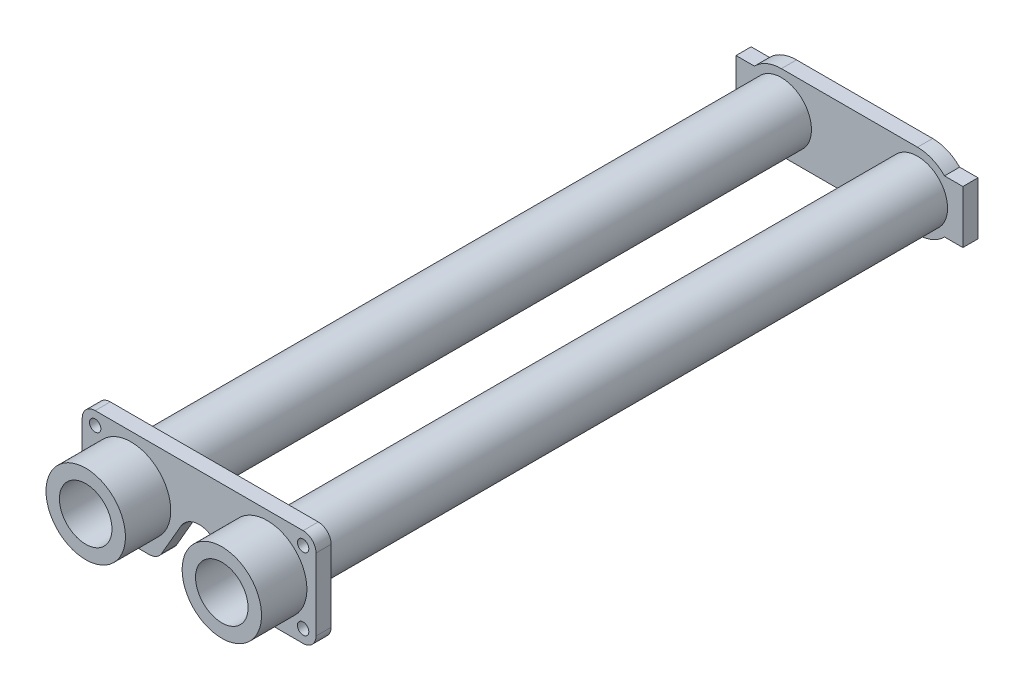
SolidWorks part; units mm, degrees
ref_plane "front" through (0, 0, 0) normal (0, 0, 1) x (1, 0, 0)
ref_plane "top" through (0, 0, 0) normal (0, 1, 0) x (1, 0, 0)
ref_plane "right" through (0, 0, 0) normal (1, 0, 0) x (0, 0, -1)
sketch "L2D Layout front." plane through (0, 0, 0) normal (0, 0, 1) x (1, 0, 0)
  line L0 (87.3125, 41.021) -> (-87.3125, 41.021)
  line L1 (-98.171, 30.1625) -> (-98.171, -30.1625)
  line L2 (-87.3125, -41.021) -> (-42.161, -41.021)
  line L3 (98.171, -30.1625) -> (98.171, 30.1625)
  line L5 (-87.3125, -38.4187) -> (-80.1624, -34.2906) construction
  line L6 (-80.1624, -34.2906) -> (-80.1624, -26.0344) construction
  line L7 (-80.1624, -26.0344) -> (-87.3125, -21.9063) construction
  line L8 (-87.3125, -21.9063) -> (-94.4626, -26.0344) construction
  line L9 (-94.4626, -26.0344) -> (-94.4626, -34.2906) construction
  line L10 (-94.4626, -34.2906) -> (-87.3125, -38.4187) construction
  line L11 (-15.3429, -7.0167) -> (-31.3825, -34.798)
  line L12 (31.3825, -34.798) -> (15.3429, -7.0168)
  line L13 (42.161, -41.021) -> (87.3125, -41.021)
  line L14 (0, -20.3188) -> (0, -32.9867) construction
  arc A0 (87.3125, 41.021) -> (98.171, 30.1625) centre (87.3125, 30.1625) cw
  circle A1 centre (-57.15, 0) radius 25.2349
  circle A2 centre (-87.3125, -30.1625) radius 7.9375 construction
  circle A3 centre (-87.3125, -30.1625) radius 7.1501 construction
  arc A4 (-87.3125, 41.021) -> (-98.171, 30.1625) centre (-87.3125, 30.1625) ccw
  arc A5 (-98.171, -30.1625) -> (-87.3125, -41.021) centre (-87.3125, -30.1625) ccw
  arc A6 (87.3125, -41.021) -> (98.171, -30.1625) centre (87.3125, -30.1625) ccw
  circle A7 centre (0, 15.875) radius 6.3627
  circle A8 centre (-87.3125, -30.1625) radius 4.7879
  circle A9 centre (-87.3125, 30.1625) radius 4.7879
  circle A10 centre (87.3125, -30.1625) radius 4.7879
  circle A11 centre (87.3125, 30.1625) radius 4.7879
  circle A13 centre (57.15, 0) radius 25.2349
  circle A14 centre (0, 15.875) radius 9.525
  circle A15 centre (57.15, 0) radius 33.3375
  circle A16 centre (-57.15, 0) radius 33.3375
  arc A17 (15.3429, -7.0168) -> (-15.3429, -7.0167) centre (0, -15.875) ccw
  arc A18 (-42.161, -41.021) -> (-31.3825, -34.798) centre (-42.161, -28.575) ccw
  arc A19 (31.3825, -34.798) -> (42.161, -41.021) centre (42.161, -28.575) ccw
  circle A21 centre (-17.4752, 3.175) radius 3.175
  dimension "D1" = 10.8585
  dimension "D6" = 50.4698
  dimension "D7" = 57.15
  dimension "D12" = 9.5758
  dimension "D13" = 15.875
  dimension "D14" = 14.3002
  dimension "D18" = 12.7254
  dimension "D19" = 19.05
  dimension "D17" = 66.675
  dimension "D21" = 17.7165
  dimension "D22" = 12.446
  dimension "D26" = 17.4752
  dimension "D16" = 6.35
  dimension "D2" = 196.342
  dimension "D3" = 87.3125
  dimension "D4" = 15.875
  dimension "D5" = 57.15
  dimension "D8" = 30.1625
  dimension "D9" = 174.625
  dimension "D10" = 87.3125
  dimension "D11" = 30.1625
  dimension "D15" = 82.042
  dimension "D20" = 15.875
  dimension "D23" = 30
  dimension "D24" = 30
  dimension "D25" = 3.175
sketch "Sketch1" plane through (0, 0, 0) normal (0, 0, 1) x (1, 0, 0)
  line L0 (-98.171, 30.1625) -> (-98.171, -30.1625) construction
  line L5 (-87.3125, -41.021) -> (-42.161, -41.021) construction
  line L6 (-15.3429, -7.0167) -> (-31.3825, -34.798) construction
  line L7 (31.3825, -34.798) -> (15.3429, -7.0168) construction
  line L8 (42.161, -41.021) -> (87.3125, -41.021) construction
  line L9 (98.171, -30.1625) -> (98.171, 30.1625) construction
  line L10 (87.3125, 41.021) -> (-87.3125, 41.021) construction
  line L11 (-98.171, 30.1625) -> (-98.171, -30.1625)
  line L12 (-87.3125, -41.021) -> (-42.161, -41.021)
  line L13 (-15.3429, -7.0167) -> (-31.3825, -34.798)
  line L14 (31.3825, -34.798) -> (15.3429, -7.0168)
  line L15 (42.161, -41.021) -> (87.3125, -41.021)
  line L16 (98.171, -30.1625) -> (98.171, 30.1625)
  line L17 (87.3125, 41.021) -> (-87.3125, 41.021)
  arc A4 (-87.3125, 41.021) -> (-98.171, 30.1625) centre (-87.3125, 30.1625) ccw construction
  arc A5 (-98.171, -30.1625) -> (-87.3125, -41.021) centre (-87.3125, -30.1625) ccw construction
  arc A6 (-42.161, -41.021) -> (-31.3825, -34.798) centre (-42.161, -28.575) ccw construction
  arc A7 (15.3429, -7.0168) -> (-15.3429, -7.0167) centre (0, -15.875) ccw construction
  arc A8 (31.3825, -34.798) -> (42.161, -41.021) centre (42.161, -28.575) ccw construction
  arc A9 (87.3125, -41.021) -> (98.171, -30.1625) centre (87.3125, -30.1625) ccw construction
  arc A10 (98.171, 30.1625) -> (87.3125, 41.021) centre (87.3125, 30.1625) ccw construction
  arc A11 (-87.3125, 41.021) -> (-98.171, 30.1625) centre (-87.3125, 30.1625) ccw
  arc A12 (-98.171, -30.1625) -> (-87.3125, -41.021) centre (-87.3125, -30.1625) ccw
  arc A13 (-42.161, -41.021) -> (-31.3825, -34.798) centre (-42.161, -28.575) ccw
  arc A14 (15.3429, -7.0168) -> (-15.3429, -7.0167) centre (0, -15.875) ccw
  arc A15 (31.3825, -34.798) -> (42.161, -41.021) centre (42.161, -28.575) ccw
  arc A16 (87.3125, -41.021) -> (98.171, -30.1625) centre (87.3125, -30.1625) ccw
  arc A17 (98.171, 30.1625) -> (87.3125, 41.021) centre (87.3125, 30.1625) ccw
extrude "Extrude1" add sketch "Sketch1" against normal blind 12.7
sketch "Sketch27" plane through (0, 0, 0) normal (0, 0, 1) x (1, 0, 0)
  circle A2 centre (57.15, 0) radius 33.3375 construction
  circle A3 centre (-57.15, 0) radius 33.3375 construction
  circle A4 centre (-57.15, 0) radius 33.3375
  circle A5 centre (57.15, 0) radius 33.3375
  point P6 (-57.15, 33.3375)
  point P7 (57.15, 33.3375)
extrude "Extrude3" add sketch "Sketch27" along normal blind 38.1
sketch "Sketch29" plane through (0, 0, 0) normal (0, 0, 1) x (1, 0, 0)
  circle A0 centre (-87.3125, -30.1625) radius 4.7879 construction
  circle A1 centre (87.3125, -30.1625) radius 4.7879 construction
  circle A2 centre (87.3125, 30.1625) radius 4.7879 construction
  circle A3 centre (-87.3125, 30.1625) radius 4.7879 construction
  circle A4 centre (57.15, 0) radius 25.2349 construction
  circle A6 centre (-57.15, 0) radius 25.2349 construction
  circle A7 centre (-87.3125, -30.1625) radius 4.7879
  circle A8 centre (87.3125, -30.1625) radius 4.7879
  circle A9 centre (87.3125, 30.1625) radius 4.7879
  circle A10 centre (-87.3125, 30.1625) radius 4.7879
  circle A11 centre (57.15, 0) radius 25.2349
  circle A13 centre (-57.15, 0) radius 25.2349
extrude "Cut-Extrude5" cut sketch "Sketch29" against normal mid plane 101.6
sketch "Sketch41" plane through (0, 0, 38.1) normal (0, 0, -1) x (-1, 0, 0)
  circle A0 centre (-57.15, 0) radius 25.2349 construction
  circle A1 centre (57.15, 0) radius 25.2349 construction
  circle A2 centre (-57.15, 0) radius 25.2349
  circle A3 centre (57.15, 0) radius 25.2349
  circle A6 centre (-57.15, 0) radius 22.0599
  circle A7 centre (-57.15, 0) radius 22.0599
  circle A9 centre (57.15, 0) radius 22.0599
  circle A10 centre (57.15, 0) radius 22.0599
  dimension "D1" = 3.175
  dimension "D2" = 3.175
extrude "Boss-Extrude1" add sketch "Sketch41" along normal blind 596.9
sketch "Sketch42" plane through (0, 0, -558.8) normal (0, 0, -1) x (-1, 0, 0)
  line L0 (57.15, 31.75) -> (-57.15, 31.75)
  line L1 (-79.824, 22.225) -> (-95.25, 22.225)
  line L2 (-95.25, 22.225) -> (-95.25, -22.225)
  line L3 (0, 16.3723) -> (0, 50.3524) construction
  line L4 (57.15, -31.75) -> (-57.15, -31.75)
  line L5 (-79.824, -22.225) -> (-95.25, -22.225)
  line L6 (79.824, -22.225) -> (95.25, -22.225)
  line L7 (95.25, 22.225) -> (95.25, -22.225)
  line L8 (79.824, 22.225) -> (95.25, 22.225)
  arc A0 (-57.15, 31.75) -> (-79.824, 22.225) centre (-57.15, 0) ccw
  arc A1 (-57.15, -31.75) -> (-79.824, -22.225) centre (-57.15, 0) cw
  arc A2 (57.15, -31.75) -> (79.824, -22.225) centre (57.15, 0) ccw
  arc A3 (57.15, 31.75) -> (79.824, 22.225) centre (57.15, 0) cw
  circle A6 centre (-57.15, 0) radius 22.5679
  circle A7 centre (-57.15, 0) radius 22.5679
  circle A9 centre (57.15, 0) radius 22.5679
  circle A10 centre (57.15, 0) radius 22.5679
  point P2 (-95.25, 0)
  dimension "D2" = 31.75
  dimension "D1" = 44.45
  dimension "D3" = 38.1
  dimension "D4" = 0.508
  dimension "D5" = 0.508
extrude "Boss-Extrude2" add sketch "Sketch42" against normal blind 12.7
